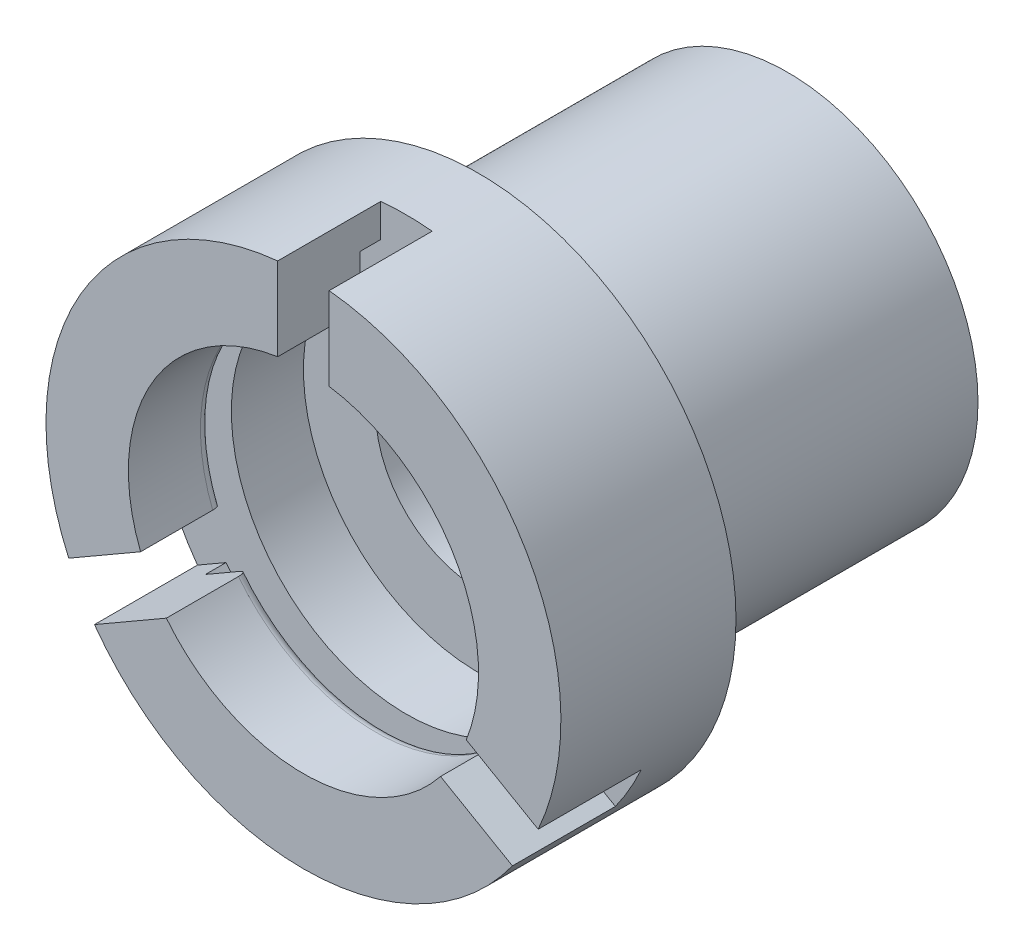
SolidWorks part; units mm, degrees
material "Nylon 101"
ref_plane "Спереди" through (0, 0, 0) normal (0, 0, 1) x (1, 0, 0)
ref_plane "Сверху" through (0, 0, 0) normal (0, 1, 0) x (1, 0, 0)
ref_plane "Справа" through (0, 0, 0) normal (1, 0, 0) x (0, 0, -1)
sketch "Эскиз1" plane through (0, 0, 0) normal (0, 0, 1) x (1, 0, 0)
  circle A4 centre (0, 0) radius 1
  circle A9 centre (0, 0) radius 1.85
  dimension "D1" = 2
  dimension "D2" = 3.7
extrude "Бобышка-Вытянуть3" add sketch "Эскиз1" along normal blind 3
sketch "Эскиз4" plane through (0, 0, 3) normal (0, 0, 1) x (1, 0, 0)
  circle A0 centre (0, 0) radius 2.5
  circle A1 centre (0, 0) radius 1.7
  dimension "D1" = 5
  dimension "D2" = 3.4
extrude "Бобышка-Вытянуть4" add sketch "Эскиз4" along normal blind 1.7
sketch "Эскиз5" plane through (0, 0, 4.7) normal (0, 0, 1) x (1, 0, 0)
  line L0 (0, 1.6) -> (0, 2.5) construction
  line L1 (0.25, 1.5803) -> (0.25, 2.5)
  line L2 (-0.25, 1.5803) -> (-0.25, 2.5)
  line L3 (0.25, 0) -> (0.25, 2.5) construction
  line L4 (0, 0) -> (0, 2.5) construction
  line L5 (-0.25, 0) -> (-0.25, 2.5) construction
  line L6 (1.2436, -1.0067) -> (2.0401, -1.4665)
  line L7 (1.4936, -0.5737) -> (2.2901, -1.0335)
  line L8 (1.3856, -0.8) -> (2.1651, -1.25) construction
  line L9 (-1.4936, -0.5737) -> (-2.2901, -1.0335)
  line L10 (-1.2436, -1.0067) -> (-2.0401, -1.4665)
  line L11 (-1.3856, -0.8) -> (-2.1651, -1.25) construction
  circle A0 centre (0, 0) radius 2.5 construction
  arc A1 (0.25, 2.5) -> (-0.25, 2.5) centre (0, 0) ccw
  arc A2 (0.25, 1.5803) -> (-0.25, 1.5803) centre (0, 0) ccw
  arc A3 (2.0401, -1.4665) -> (2.2901, -1.0335) centre (0, 0) ccw
  arc A4 (1.2436, -1.0067) -> (1.4936, -0.5737) centre (0, 0) ccw
  arc A5 (-2.2901, -1.0335) -> (-2.0401, -1.4665) centre (0, 0) ccw
  arc A6 (-1.4936, -0.5737) -> (-1.2436, -1.0067) centre (0, 0) ccw
  point P26 (0, 0)
extrude "Вырез-Вытянуть3" cut sketch "Эскиз5" against normal blind 1
sketch "Эскиз7" plane through (0, 0, 0) normal (1, 0, 0) x (0, 0, -1)
  line L0 (-3.7, 1.6815) -> (-4.7, 1.6815) construction
  line L1 (-3.7, 1.6815) -> (-3.9, 1.6815)
  line L2 (-3.7, 1.6815) -> (-3.7, 2.1815)
  line L3 (-3.7, 2.1815) -> (-3.9, 2.1815)
  line L4 (-3.9, 1.6815) -> (-3.9, 2.1815)
  line L5 (0, 0) -> (-4.7, 0) construction
  line L6 (-4.7, 1.6815) -> (-4.7, -0.6243) construction
  dimension "D1" = 0.2
  dimension "D2" = 0.5
revolve "Вырез-Повернуть1" cut sketch "Эскиз7" angle 360 about L5
fillet "Скругление1" radius 0.1 3 edges at (1.4722, 0.85, 3.9) (-1.4722, 0.85, 3.9) (0, -1.7, 3.9)
